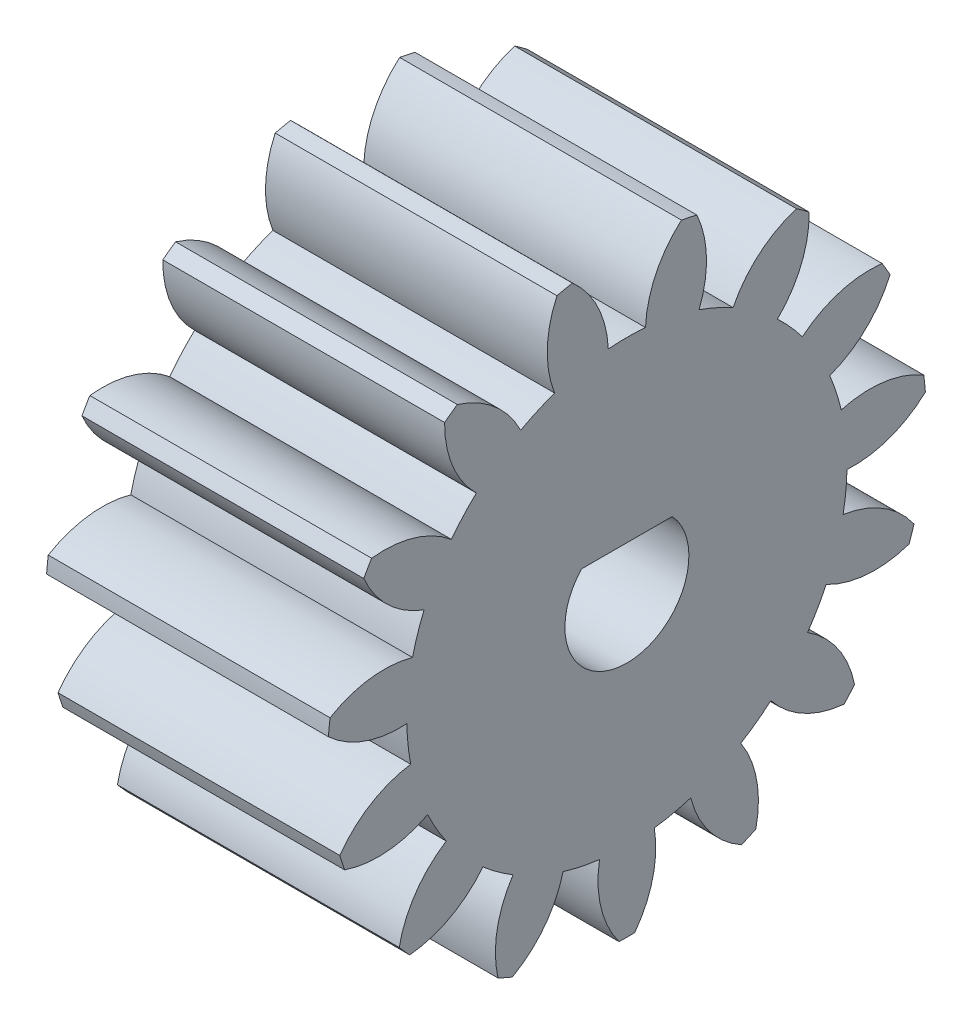
SolidWorks part; units mm, degrees
ref_plane "Plane1" through (0, 0, 0) normal (0, 0, 1) x (1, 0, 0)
ref_plane "Plane2" through (0, 0, 0) normal (0, 1, 0) x (1, 0, 0)
ref_plane "Plane3" through (0, 0, 0) normal (1, 0, 0) x (0, 0, -1)
sketch "HoldingSke" plane through (0, 0, 0) normal (0, 1, 0) x (1, 0, 0)
  line L0 (0, 0) -> (0.7727, -0.2071)
  line L1 (-15, 0) -> (100, 0) construction
  line L2 (0, 0) -> (-2.1039, 2.3779)
  line L3 (0, 0) -> (-11.863, 4.5341)
  line L4 (0, 0) -> (8.3417, 2.2352)
  line L5 (0, 0) -> (-46.8476, -17.4728)
  line L6 (0, 0) -> (-8.2896, -5.593)
  line L7 (-2.1039, 2.3779) -> (8.6586, 51.2059)
  line L8 (-76.2, 54.61) -> (-75.5, 54.61)
  line L9 (-71.009, 38.7566) -> (-53.1078, 45.2721)
  line L10 (-76.2, 71.12) -> (104.1128, 71.12)
  line L11 (0, 0) -> (-10, 0)
  line L12 (-76.2, 101.6) -> (-76.155, 101.6)
  line L13 (24.9733, 27.94) -> (52.9518, 28.4284)
  line L14 (24.9733, 27.94) -> (24.9743, 27.94)
  line L15 (24.9733, 27.94) -> (100.4006, 29.5858)
  line L16 (-63.627, -1.25) -> (-12.827, -1.25)
  circle A0 centre (0, 0) radius 2
  circle A1 centre (0, 0) radius 7.8115
  circle A2 centre (0, 0) radius 37.5
  circle A3 centre (0, 0) radius 2
  dimension "MHD" = 15.623
  dimension "Hub_dia" = 75
  dimension "Bore" = 4
  dimension "MBD" = 4
  dimension "Num_teeth" = 15
  dimension "Pitch" = 0.8
  dimension "Overall_len" = 50
  dimension "Show_teeth" = 15
  dimension "Thickness" = 10
  dimension "OAL" = 50.0001
  dimension "T_dim" = 0.7
  dimension "Ap" = 20
  dimension "H" = 19.05
  dimension "Pitch_radius" = 180.3128
  dimension "Width" = 10
  dimension "Backlash" = 0.045
  dimension "Addendum_fac" = 1
  dimension "Dedendum_fac" = 1.25
  dimension "Clearance_fac" = 0.25
  dimension "Dedendum_add" = 0.001
  dimension "Module" = 1.25
sketch "BasProSke" plane through (0, 0, 0) normal (0, 1, 0) x (1, 0, 0)
  line L0 (-10, 0) -> (60, 0) construction
  line L1 (0, 0) -> (0, 10.625)
  line L2 (0, 0) -> (10, 0)
  line L3 (10, 0) -> (10, 10.625)
  line L4 (10, 10.625) -> (0, 10.625)
  dimension "Thickness" = 10
  dimension "Diameter" = 21.25
revolve "Base-Revolve" add sketch "BasProSke" angle 360 about L0
sketch "TooCutSke" plane through (0, 0, 0) normal (1, 0, 0) x (0, 0, -1)
  line L1 (0, 0) -> (0, 107) construction
  line L2 (0, 0) -> (-1.0586, 9.315) construction
  line L3 (0, 0) -> (-3.8803, 18.2553) construction
  line L4 (-1.0586, 9.315) -> (-1.9401, 9.1277) construction
  arc A0 (0.6608, 7.7835) -> (-0.6608, 7.7835) centre (0, 0) ccw
  arc A1 (1.9597, 10.4686) -> (-1.9597, 10.4686) centre (0, 0) ccw
  circle A2 centre (0, 0) radius 9.375 construction
  circle A3 centre (0, 0) radius 8.8096 construction
  arc A4 (-0.6608, 7.7835) -> (-1.9597, 10.4686) centre (-4.4076, 7.6277) ccw
  arc A5 (1.9597, 10.4686) -> (0.6608, 7.7835) centre (4.4076, 7.6277) ccw
  dimension "Root_dia" = 15.623
  dimension "Overcut_dia" = 21.3008
  dimension "Pitch_dia" = 18.75
  dimension "Base_dia" = 17.6192
  dimension "Flank_rad" = 3.75
  dimension "Half_ang" = 12
  dimension "Half_CT" = 0.9012
extrude "ToothCut" cut sketch "TooCutSke" along normal through all
fillet "Breaks" [suppressed] radius 0.025
fillet "RootFillets" [suppressed] radius 0.3135
pattern_circular "TeethCuts" count 15 every 24 about axis through (-10, 0, 0) along (1, 0, 0) of "ToothCut", "RootFillets", "Breaks"
sketch "HubNeaOneSke" plane through (0, 0, 0) normal (-1, 0, 0) x (0, 0, 1)
  circle A0 centre (0, 0) radius 7.8115
  dimension "Diameter" = 15.623
extrude "HubNearOne" [suppressed] add sketch "HubNeaOneSke" along normal blind 40.0001
sketch "HubNeaBotSke" plane through (0, 0, 0) normal (-1, 0, 0) x (0, 0, 1)
  circle A0 centre (0, 0) radius 7.8115
  dimension "Diameter" = 15.623
extrude "HubNearBoth" [suppressed] add sketch "HubNeaBotSke" along normal blind 20
ref_plane "FarPln" through (10, 0, 0) normal (1, 0, 0) x (0, 0, -1)
sketch "HubFarSke" plane through (10, 0, 0) normal (1, 0, 0) x (0, 0, -1)
  circle A0 centre (0, 0) radius 7.8115
  dimension "Diameter" = 15.623
extrude "HubFar" [suppressed] add sketch "HubFarSke" along normal blind 20
sketch "BorSke" plane through (0, 0, 0) normal (1, 0, 0) x (0, 0, -1)
  circle A0 centre (0, 0) radius 2
  dimension "Diameter" = 4
extrude "Bore" cut sketch "BorSke" along normal mid plane 100.0001
sketch "KeySke" plane through (0, 0, 0) normal (1, 0, 0) x (0, 0, -1)
  line L0 (-0.8, 0) -> (-0.8, 2.7)
  line L1 (-0.8, 2.7) -> (0.8, 2.7)
  line L2 (0.8, 2.7) -> (0.8, 0)
  line L3 (0, 0) -> (0, 34) construction
  line L4 (-0.8, 0) -> (0.8, 0)
  dimension "Offset" = 2.7
  dimension "Width" = 1.6
extrude "Keyway" [suppressed] cut sketch "KeySke" along normal mid plane 100.0001
pattern_circular "Keyway2" [suppressed] count 2 every 90 about axis through (-10, 0, 0) along (1, 0, 0)
sketch "Sketch1" plane through (10, 0, 0) normal (1, 0, 0) x (0, 0, -1)
  circle A0 centre (0, 0) radius 2.2
  dimension "D1" = 4.4
extrude "Cut-Extrude2" cut sketch "Sketch1" against normal blind 10
sketch "Sketch4" plane through (10, 0, 0) normal (1, 0, 0) x (0, 0, -1)
  line L0 (0, -2.2) -> (0, 1.5) construction
  line L1 (-1.6093, 1.5) -> (1.6093, 1.5)
  circle A0 centre (0, 0) radius 2.2 construction
  arc A1 (-1.6093, 1.5) -> (1.6296, 1.4779) centre (0, 0) cw
extrude "Boss-Extrude1" add sketch "Sketch4" against normal blind 10 contours A1 L1
equation "' \"Module@HoldingSke\" = 6.35"
equation "' \"Num_teeth@HoldingSke\" = 12"
equation "' \"Ap@HoldingSke\" =  20"
equation "' \"Ap@HoldingSke\" = 20"
equation "' \"Width@HoldingSke\" = 0.5 * 25.4"
equation "' \"Hub_dia@HoldingSke\"= 1 * 25.4"
equation "' \"Hub_dia@HoldingSke\" = 1 * 25.4"
equation "' \"Overall_len@HoldingSke\" = 1.0 * 25.4"
equation "' \"Bore@HoldingSke\" = 0.75 * 25.4"
equation "' \"T_dim@HoldingSke\" = 0.1 * 25.4"
equation "' \"Width@KeySke\" = 0.25 * 25.4"
equation "' \"Show_teeth@HoldingSke\" = 13"
equation "' \"Backlash@HoldingSke\" = 0.009 * 25.4"
equation "' \"Addendum_fac@HoldingSke\" = 1.0"
equation "' \"Dedendum_fac@HoldingSke\" = 1.25"
equation "' \"Dedendum_add@HoldingSke\" = 0.00005 * 25.4"
equation "' \"Clearance_fac@HoldingSke\" = 0.25"
equation "\"Pitch@HoldingSke\" = 1 / \"Module@HoldingSke\""
equation "\"Overcut_dia@TooCutSke\" = (\"Num_teeth@HoldingSke\" + 2 * \"Addendum_fac@HoldingSke\") / \"Pitch@HoldingSke\" + 0.002 * 25.4"
equation "\"Pitch_dia@TooCutSke\" = \"Num_teeth@HoldingSke\" / \"Pitch@HoldingSke\""
equation "\"Base_dia@TooCutSke\" = \"Num_teeth@HoldingSke\" / \"Pitch@HoldingSke\" * cos((\"Ap@HoldingSke\"  * 3.14159265 / 180))"
equation "\"Root_dia@TooCutSke\" = (\"Num_teeth@HoldingSke\" + 2) / \"Pitch@HoldingSke\" - 2 * (\"Addendum_fac@HoldingSke\" + \"Dedendum_fac@HoldingSke\") / \"Pitch@HoldingSke\" - \"Dedendum_add@HoldingSke\" * 2"
equation "\"Half_ang@TooCutSke\" = 180 / \"Num_teeth@HoldingSke\""
equation "\"Half_CT@TooCutSke\" = \"Num_teeth@HoldingSke\" / \"Pitch@HoldingSke\" * sin((3.14159265 / 2 / \"Num_teeth@HoldingSke\")) / 2 - 7 * \"Backlash@HoldingSke\" / 4"
equation "\"Flank_rad@TooCutSke\" = \"Num_teeth@HoldingSke\" / \"Pitch@HoldingSke\" / 5"
equation "\"Radius@RootFillets\" = \"Clearance_fac@HoldingSke\" / \"Pitch@HoldingSke\" + \"Dedendum_add@HoldingSke\""
equation "\"Break_rad@Breaks\" = 0.02 / \"Pitch@HoldingSke\""
equation "\"Thickness@HoldingSke\" = \"Width@HoldingSke\""
equation "\"OAL@HoldingSke\" = \"Thickness@HoldingSke\""
equation "\"MHD@HoldingSke\" = (\"Num_teeth@HoldingSke\" + 2) / \"Pitch@HoldingSke\" - 2 * (\"Addendum_fac@HoldingSke\" + \"Dedendum_fac@HoldingSke\")  / \"Pitch@HoldingSke\" - \"Dedendum_add@HoldingSke\" * 2"
equation "\"MBD@HoldingSke\" = (\"Num_teeth@HoldingSke\" + 2) / \"Pitch@HoldingSke\" - 2 * (\"Addendum_fac@HoldingSke\" + \"Dedendum_fac@HoldingSke\")  / \"Pitch@HoldingSke\" - \"Dedendum_add@HoldingSke\" * 2 - 0.002 * 25.4"
equation "\"MHD@HoldingSke\" = ((sgn( \"MHD@HoldingSke\" - \"Hub_dia@HoldingSke\" )-1)*( \"MHD@HoldingSke\" - \"Hub_dia@HoldingSke\" ))/-2+ \"Hub_dia@HoldingSke\""
equation "\"MBD@HoldingSke\" = ((sgn( \"MBD@HoldingSke\" - \"Bore@HoldingSke\" )-1)*( \"MBD@HoldingSke\" - \"Bore@HoldingSke\" ))/-2+ \"Bore@HoldingSke\""
equation "\"OAL@HoldingSke\" = ((sgn( \"OAL@HoldingSke\" - \"Overall_len@HoldingSke\" )+1)*( \"OAL@HoldingSke\" - \"Overall_len@HoldingSke\" ))/2 + \"Overall_len@HoldingSke\" + 0.000002 * 25.4"
equation "\"Num_teeth@TeethCuts\" = int( \"Show_teeth@HoldingSke\" ) + 1"
equation "\"Num_teeth@TeethCuts\" = ((sgn( \"Num_teeth@TeethCuts\" - \"Num_teeth@HoldingSke\" )-1)*( \"Num_teeth@TeethCuts\" - \"Num_teeth@HoldingSke\" ))/-2+ \"Num_teeth@HoldingSke\""
equation "\"Num_teeth@TeethCuts\" = ((sgn( \"Num_teeth@TeethCuts\" - 2.0)+1)*( \"Num_teeth@TeethCuts\" - 2.0))/2 +2.0"
equation "\"Angle@TeethCuts\" = 360.0 / \"Num_teeth@HoldingSke\""
equation "\"Diameter@BasProSke\" = (\"Num_teeth@HoldingSke\" + 2 * \"Addendum_fac@HoldingSke\") / \"Pitch@HoldingSke\""
equation "\"Thickness@BasProSke\"  = \"Thickness@HoldingSke\""
equation "' \"Fillet_rad@BasProSke\" =  \"Thickness@HoldingSke\" * 0.05"
equation "' \"Fillet_rad@BasProSke\" = \"Thickness@HoldingSke\" * 0.05"
equation "\"MHD@HoldingSke\" = ((sgn( \"MHD@HoldingSke\" - \"Root_dia@TooCutSke\" )-1)*( \"MHD@HoldingSke\" - \"Root_dia@TooCutSke\" ))/-2+ \"Root_dia@TooCutSke\""
equation "\"Diameter@HubNeaOneSke\" = \"MHD@HoldingSke\""
equation "\"Length@HubNearOne\" = \"OAL@HoldingSke\" - \"Thickness@BasProSke\""
equation "\"Diameter@HubNeaBotSke\" = \"MHD@HoldingSke\""
equation "\"Length@HubNearBoth\" = ( \"OAL@HoldingSke\" - \"Thickness@BasProSke\" ) / 2.0"
equation "\"Thickness@FarPln\" = \"Thickness@BasProSke\""
equation "\"Diameter@HubFarSke\" = \"MHD@HoldingSke\""
equation "\"Length@HubFar\" = ( \"OAL@HoldingSke\" - \"Thickness@BasProSke\" ) / 2.0"
equation "\"Diameter@BorSke\" = \"MBD@HoldingSke\""
equation "\"D1@Bore\" = \"OAL@HoldingSke\" * 2.0"
equation "\"D1@Keyway\" = \"OAL@HoldingSke\" * 2.0"
equation "\"Offset@KeySke\" = \"T_dim@HoldingSke\" + \"MBD@HoldingSke\" / 2.0"
